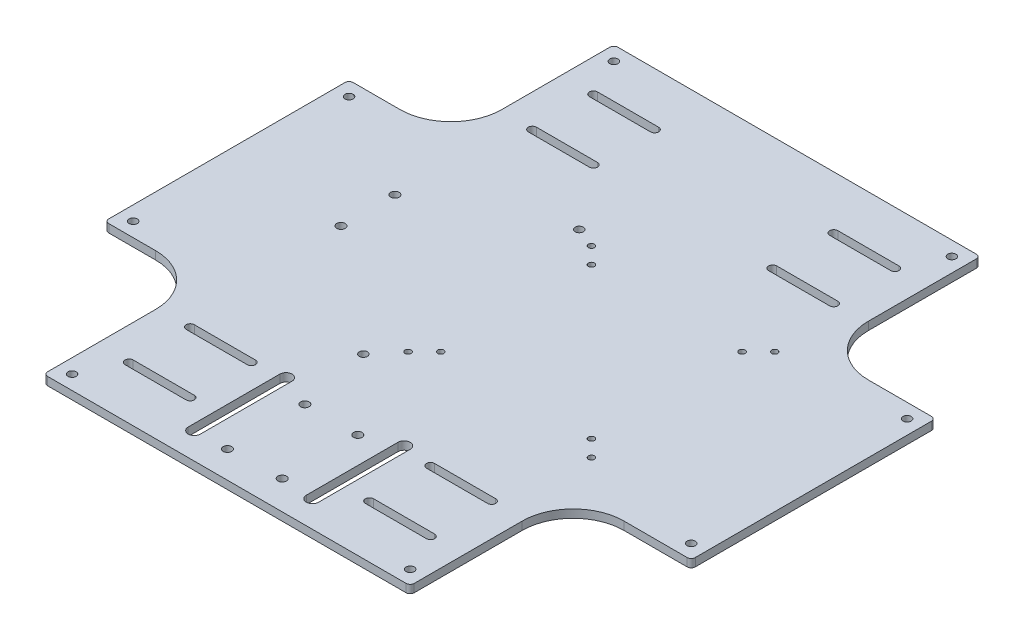
SolidWorks part; units mm, degrees
ref_plane "前视基准面" through (0, 0, 0) normal (0, 0, 1) x (1, 0, 0)
ref_plane "上视基准面" through (0, 0, 0) normal (0, 1, 0) x (1, 0, 0)
ref_plane "右视基准面" through (0, 0, 0) normal (1, 0, 0) x (0, 0, -1)
other "Configuration Table"
sketch "草图1" plane through (0, 0, 0) normal (0, 1, 0) x (1, 0, 0)
  line L0 (0, 183.6662) -> (0, -202.8181) construction
  line L1 (-90, -145) -> (90, -145)
  line L2 (-140, -65) -> (-140, 55)
  line L3 (-90, 135) -> (90, 135)
  line L4 (140, -65) -> (140, 55)
  line L5 (-204.1587, 0) -> (227.5239, 0) construction
  line L6 (90, 135) -> (90, 55)
  line L7 (90, 55) -> (140, 55)
  line L8 (90, -145) -> (90, -65)
  line L9 (90, -65) -> (140, -65)
  line L10 (-90, -145) -> (-90, -65)
  line L11 (-90, -65) -> (-140, -65)
  line L12 (-90, 55) -> (-140, 55)
  line L13 (-90, 135) -> (-90, 55)
  circle A0 centre (-83, -138) radius 2
  circle A3 centre (-83, 128) radius 2
  circle A4 centre (83, -138) radius 2
  circle A7 centre (83, 128) radius 2
  circle A8 centre (-133, 48) radius 2
  circle A9 centre (-133, -58) radius 2
  circle A10 centre (-20, 48) radius 2
  circle A11 centre (-20, -58) radius 2
  point P0 (0, 0)
  dimension "D6" = 7
  dimension "D7" = 7
  dimension "D8" = 4
  dimension "D9" = 4
  dimension "D10" = 4
  dimension "D11" = 7
  dimension "D12" = 7
  dimension "D13" = 7
  dimension "D14" = 7
  dimension "D15" = 4
  dimension "D16" = 7
  dimension "D17" = 7
  dimension "D18" = 4
  dimension "D19" = 4
  dimension "D20" = 113
  dimension "D21" = 113
  dimension "D1" = 280
  dimension "D2" = 280
  dimension "D3" = 80
  dimension "D4" = 50
  dimension "D5" = 80
extrude "凸台-拉伸1" add sketch "草图1" along normal blind 4
sketch "草图2" plane through (0, 4, 0) normal (0, 1, 0) x (1, 0, 0)
  line L0 (-90, -117) -> (-18.7145, -117) construction
  line L1 (-90, -65) -> (-90, -145) construction
  line L2 (-90, -145) -> (90, -145) construction
  line L3 (-74, -49.9921) -> (-74, -149.7465) construction
  line L4 (-93.0922, -121) -> (-18.7145, -121) construction
  line L5 (-74, -119) -> (-44, -119) construction
  line L6 (-74, -117) -> (-44, -117)
  line L7 (-74, -121) -> (-44, -121)
  line L8 (-97.2222, -89) -> (-19.948, -89) construction
  line L9 (-74, -89) -> (-44, -89) construction
  line L10 (-74, -87) -> (-44, -87)
  line L11 (-74, -91) -> (-44, -91)
  line L12 (0, 194.2077) -> (0, -228.6866) construction
  line L13 (-172.013, -5) -> (190.6916, -5) construction
  line L14 (74, -89) -> (44, -89) construction
  line L15 (74, -87) -> (44, -87)
  line L16 (74, -91) -> (44, -91)
  line L17 (74, -119) -> (44, -119) construction
  line L18 (74, -117) -> (44, -117)
  line L19 (74, -121) -> (44, -121)
  line L20 (74, 109) -> (44, 109) construction
  line L23 (74, 107) -> (44, 107)
  line L26 (74, 111) -> (44, 111)
  line L29 (74, 79) -> (44, 79) construction
  line L35 (-90, 55) -> (-140, 55) construction
  line L36 (-140, -65) -> (-90, -65) construction
  line L37 (74, 77) -> (44, 77)
  line L38 (74, 81) -> (44, 81)
  line L39 (-74, 79) -> (-44, 79) construction
  line L40 (-74, 77) -> (-44, 77)
  line L41 (-74, 81) -> (-44, 81)
  line L42 (-74, 109) -> (-44, 109) construction
  line L43 (-74, 107) -> (-44, 107)
  line L44 (-74, 111) -> (-44, 111)
  arc A0 (-74, -117) -> (-74, -121) centre (-74, -119) ccw
  arc A1 (-44, -121) -> (-44, -117) centre (-44, -119) ccw
  arc A2 (-74, -87) -> (-74, -91) centre (-74, -89) ccw
  arc A3 (-44, -91) -> (-44, -87) centre (-44, -89) ccw
  arc A4 (74, -87) -> (74, -91) centre (74, -89) cw
  arc A5 (44, -91) -> (44, -87) centre (44, -89) cw
  arc A6 (74, -117) -> (74, -121) centre (74, -119) cw
  arc A7 (44, -121) -> (44, -117) centre (44, -119) cw
  arc A16 (74, 107) -> (74, 111) centre (74, 109) ccw
  arc A17 (44, 111) -> (44, 107) centre (44, 109) ccw
  arc A18 (74, 77) -> (74, 81) centre (74, 79) ccw
  arc A19 (44, 81) -> (44, 77) centre (44, 79) ccw
  arc A20 (-74, 77) -> (-74, 81) centre (-74, 79) cw
  arc A21 (-44, 81) -> (-44, 77) centre (-44, 79) cw
  arc A22 (-74, 107) -> (-74, 111) centre (-74, 109) cw
  arc A23 (-44, 111) -> (-44, 107) centre (-44, 109) cw
  point P12 (-59, -119)
  point P21 (-59, -89)
  point P33 (59, -89)
  point P40 (59, -119)
  point P47 (59, 109)
  point P54 (59, 79)
  point P61 (-59, 79)
  point P68 (-59, 109)
  dimension "D5" = 2
  dimension "D8" = 2
  dimension "D1" = 28
  dimension "D2" = 16
  dimension "D3" = 24
  dimension "D4" = 2
  dimension "D6" = 30
  dimension "D7" = 30
  dimension "D9" = 30
extrude "切除-拉伸1" cut sketch "草图2" against normal through all both
sketch "草图3" plane through (0, 4, 0) normal (0, 1, 0) x (1, 0, 0)
  circle A0 centre (-80, 17.5292) radius 2.1
  circle A1 centre (-80, -9) radius 2.1
extrude "切除-拉伸2" cut sketch "草图3" against normal through all both
sketch "草图4" plane through (0, 4, 0) normal (0, 1, 0) x (1, 0, 0)
  line L3 (140, -65) -> (140, 55)
  line L4 (140, -65) -> (148, -65)
  line L5 (148, -65) -> (148, 55)
  line L6 (148, 55) -> (140, 55)
  dimension "D1" = 8
extrude "凸台-拉伸2" add sketch "草图4" against normal blind 4
sketch "草图6" plane through (0, 0, 0) normal (0, -1, 0) x (1, 0, 0)
  line L2 (90, 65) -> (148, 65) construction
  line L3 (148, 65) -> (148, -55) construction
  line L4 (148, -55) -> (90, -55) construction
  circle A1 centre (141, 58) radius 2
  circle A2 centre (141, -48) radius 2
  dimension "D1" = 4
  dimension "D2" = 7
  dimension "D3" = 7
  dimension "D4" = 4
  dimension "D5" = 7
  dimension "D6" = 7
extrude "切除-拉伸4" cut sketch "草图6" against normal through all both
sketch "草图7" plane through (0, 4, 0) normal (0, 1, 0) x (1, 0, 0)
  line L0 (-29, -87) -> (-29, -132) construction
  line L1 (-26, -87) -> (-26, -132)
  line L2 (-32, -87) -> (-32, -132)
  line L3 (29, -87) -> (29, -132) construction
  line L4 (32, -87) -> (32, -132)
  line L5 (26, -87) -> (26, -132)
  line L6 (-90, -145) -> (90, -145) construction
  line L7 (-21, -78) -> (21, -78) construction
  arc A0 (-26, -87) -> (-32, -87) centre (-29, -87) ccw
  arc A1 (-32, -132) -> (-26, -132) centre (-29, -132) ccw
  arc A2 (32, -87) -> (26, -87) centre (29, -87) ccw
  arc A3 (26, -132) -> (32, -132) centre (29, -132) ccw
  point P2 (-29, -109.5)
  point P9 (29, -109.5)
  point P19 (0, -78)
  dimension "D7" = 3
  dimension "D8" = 3
  dimension "D1" = 13
  dimension "D2" = 13
  dimension "D3" = 45
  dimension "D4" = 45
  dimension "D5" = 29
  dimension "D6" = 29
extrude "切除-拉伸5" cut sketch "草图7" against normal through all
sketch "草图9" plane through (0, 76, 0) normal (0, 1, 0) x (1, 0, 0)
  line L0 (148, -63) -> (148, 53) construction
  line L1 (72, -38) -> (-2, -38) construction
  line L2 (72, -38) -> (72, 36) construction
  line L3 (72, 36) -> (-2, 36) construction
  line L4 (-2, -38) -> (-2, 36) construction
  line L5 (72, -38) -> (-2, 36) construction
  line L6 (72, 36) -> (-2, -38) construction
  line L13 (88, 135) -> (-88, 135) construction
  line L15 (80, -46) -> (-10, -46) construction
  line L16 (80, -46) -> (80, 44) construction
  line L17 (80, 44) -> (-10, 44) construction
  line L18 (-10, -46) -> (-10, 44) construction
  line L19 (80, -46) -> (-10, 44) construction
  line L20 (80, 44) -> (-10, -46) construction
  circle A0 centre (72, -38) radius 1.5
  circle A1 centre (-2, -38) radius 1.5
  circle A2 centre (72, 36) radius 1.5
  circle A3 centre (-2, 36) radius 1.5
  circle A4 centre (80, -46) radius 1.5
  circle A5 centre (-10, -46) radius 1.5
  circle A6 centre (-10, 44) radius 1.5
  circle A7 centre (80, 44) radius 1.5
  point P0 (35, -1)
  point P16 (35, -1)
  dimension "D3" = 3
  dimension "D1" = 74
  dimension "D2" = 74
  dimension "D4" = 113
  dimension "D5" = 136
  dimension "D6" = 90
  dimension "D7" = 90
extrude "切除-拉伸6" cut sketch "草图9" against normal through all both
fillet "圆角1" radius 2 8 edges at (90, 2, -135) (-90, 2, -135) (-140, 2, -55) (-140, 2, 65) (-90, 2, 145) (90, 2, 145) (148, 2, -55) (148, 2, 65)
fillet "圆角2" radius 25 4 edges at (-90, 2, -55) (-90, 2, 65) (90, 2, 65) (90, 2, -55)
sketch "草图11" plane through (0, 4, 0) normal (0, 1, 0) x (1, 0, 0)
  circle A0 centre (-13, -131.7147) radius 2.1
  circle A1 centre (13, -130.8516) radius 2.1
  circle A2 centre (13, -93.7147) radius 2.1
  circle A3 centre (-13, -93.7147) radius 2.1
extrude "切除-拉伸7" cut sketch "草图11" against normal blind 10
